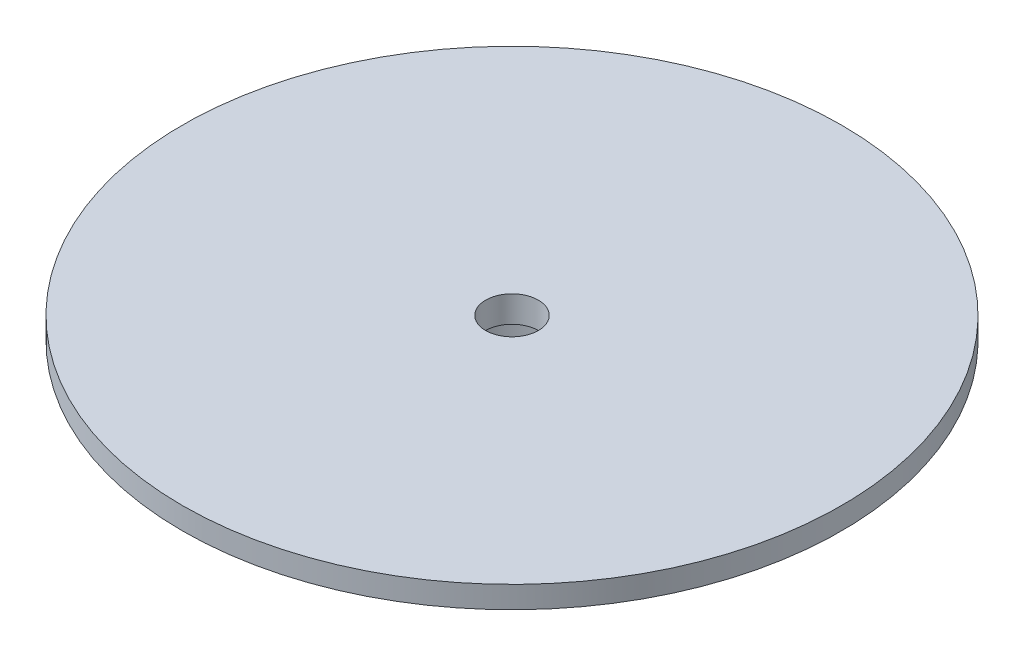
SolidWorks part; units mm, degrees
ref_plane "Plan de face" through (0, 0, 0) normal (0, 0, 1) x (1, 0, 0)
ref_plane "Plan de dessus" through (0, 0, 0) normal (0, 1, 0) x (1, 0, 0)
ref_plane "Plan de droite" through (0, 0, 0) normal (1, 0, 0) x (0, 0, -1)
sketch "Esquisse1" plane through (0, 0, 0) normal (0, 1, 0) x (1, 0, 0)
  circle A0 centre (0, 0) radius 41
  circle A1 centre (0, 0) radius 6
  dimension "D1" = 12
  dimension "D2" = 82
extrude "Boss.-Extru.1" add sketch "Esquisse1" along normal blind 10
sketch "Esquisse2" plane through (0, 0, 0) normal (0, -1, 0) x (1, 0, 0)
  circle A0 centre (0, 0) radius 17.5
  dimension "D1" = 35
extrude "Enlèv. mat.-Extru.1" cut sketch "Esquisse2" against normal blind 4
sketch "Esquisse3" plane through (0, 10, 0) normal (0, 1, 0) x (1, 0, 0)
  circle A0 centre (0, 0) radius 75
  circle A1 centre (0, 0) radius 6
  dimension "D1" = 150
extrude "Boss.-Extru.2" add sketch "Esquisse3" against normal blind 5
sketch "Esquisse4" plane through (0, 0, 0) normal (0, -1, 0) x (1, 0, 0)
  circle A0 centre (0, 0) radius 25
  circle A1 centre (0, 0) radius 17.5
  dimension "D1" = 35
  dimension "D2" = 50
extrude "Boss.-Extru.3" add sketch "Esquisse4" along normal blind 6.83
